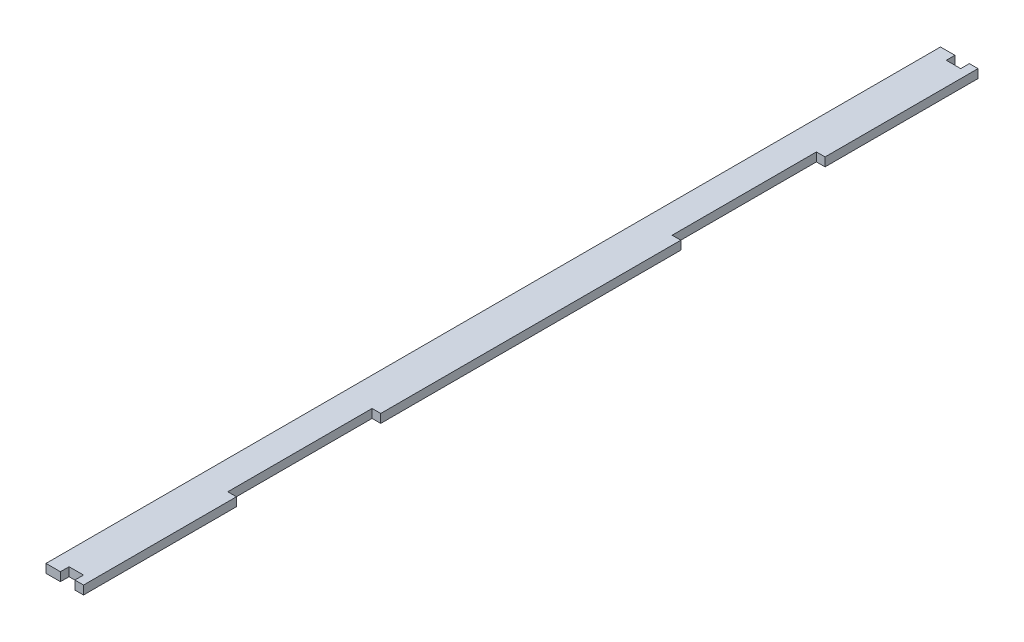
SolidWorks part; units mm, degrees
material "아크릴(내충격성)"
ref_plane "정면" through (0, 0, 0) normal (0, 0, 1) x (1, 0, 0)
ref_plane "윗면" through (0, 0, 0) normal (0, 1, 0) x (1, 0, 0)
ref_plane "우측면" through (0, 0, 0) normal (1, 0, 0) x (0, 0, -1)
sketch "스케치1" plane through (0, 0, 0) normal (0, 1, 0) x (1, 0, 0)
  line L0 (6.4093, -130.1543) -> (6.4093, -127.1543)
  line L1 (1.4093, 179.8457) -> (6.4093, 179.8457)
  line L2 (1.4093, 179.8457) -> (1.4093, -130.1543)
  line L15 (126.1881, 25) -> (-126.1881, 25) construction
  line L41 (1.4093, -130.1543) -> (6.4093, -130.1543)
  line L42 (14.4093, 179.8457) -> (14.4093, 126.8457)
  line L43 (6.4093, -127.1543) -> (11.4093, -127.1543)
  line L44 (11.4093, -127.1543) -> (11.4093, -130.1543)
  line L45 (11.4093, -130.1543) -> (14.4093, -130.1543)
  line L46 (6.4093, 179.8457) -> (6.4093, 176.8457)
  line L47 (6.4093, 176.8457) -> (11.4093, 176.8457)
  line L48 (11.4093, 176.8457) -> (11.4093, 179.8457)
  line L49 (11.4093, 179.8457) -> (14.4093, 179.8457)
  line L50 (11.4093, -130.1543) -> (11.4093, 179.8457) construction
  line L51 (14.4093, 126.8457) -> (11.4093, 126.8457)
  line L52 (11.4093, 126.8457) -> (11.4093, 76.8457)
  line L53 (11.4093, 76.8457) -> (14.4093, 76.8457)
  line L54 (14.4093, 76.8457) -> (14.4093, -27.1543)
  line L55 (11.4093, -27.1543) -> (14.4093, -27.1543)
  line L56 (14.4093, -77.1543) -> (14.4093, -130.1543)
  line L57 (14.4093, -77.1543) -> (11.4093, -77.1543)
  line L58 (11.4093, -77.1543) -> (11.4093, -27.1543)
  dimension "D1" = 13
  dimension "D2" = 310
  dimension "D3" = 3
  dimension "D4" = 3
  dimension "D5" = 5
  dimension "D6" = 5
  dimension "D7" = 3
  dimension "D8" = 3
  dimension "D9" = 53
  dimension "D10" = 53
  dimension "D11" = 50
  dimension "D12" = 50
extrude "보스-돌출1" add sketch "스케치1" along normal blind 3
